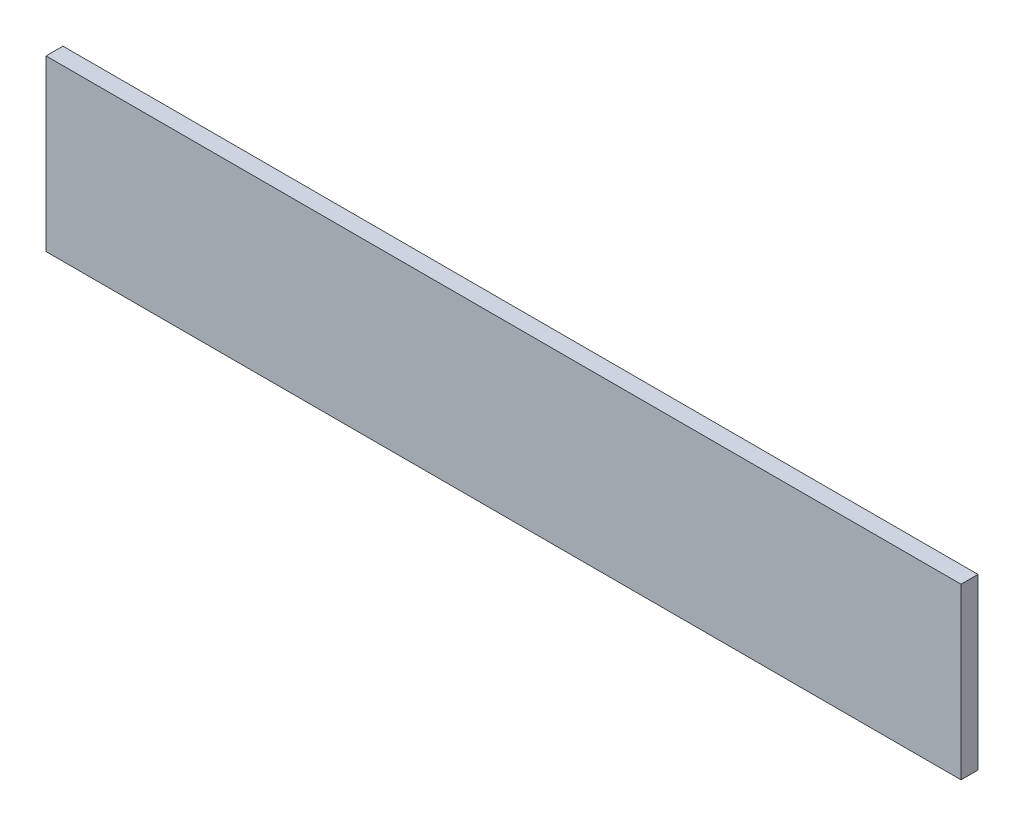
SolidWorks part; units mm, degrees
ref_plane "Plan de face" through (0, 0, 0) normal (0, 0, 1) x (1, 0, 0)
ref_plane "Plan de dessus" through (0, 0, 0) normal (0, 1, 0) x (1, 0, 0)
ref_plane "Plan de droite" through (0, 0, 0) normal (1, 0, 0) x (0, 0, -1)
sketch "Esquisse1" plane through (0, 0, 0) normal (0, 0, 1) x (1, 0, 0)
  line L1 (-135, 25) -> (135, 25)
  line L2 (-135, 25) -> (-135, -25)
  line L3 (-135, -25) -> (135, -25)
  line L4 (135, 25) -> (135, -25)
  line L5 (-135, 25) -> (135, -25) construction
  line L6 (-135, -25) -> (135, 25) construction
  point P0 (0, 0)
  dimension "D1" = 270
  dimension "D2" = 50
extrude "Boss.-Extru.1" add sketch "Esquisse1" along normal blind 5
